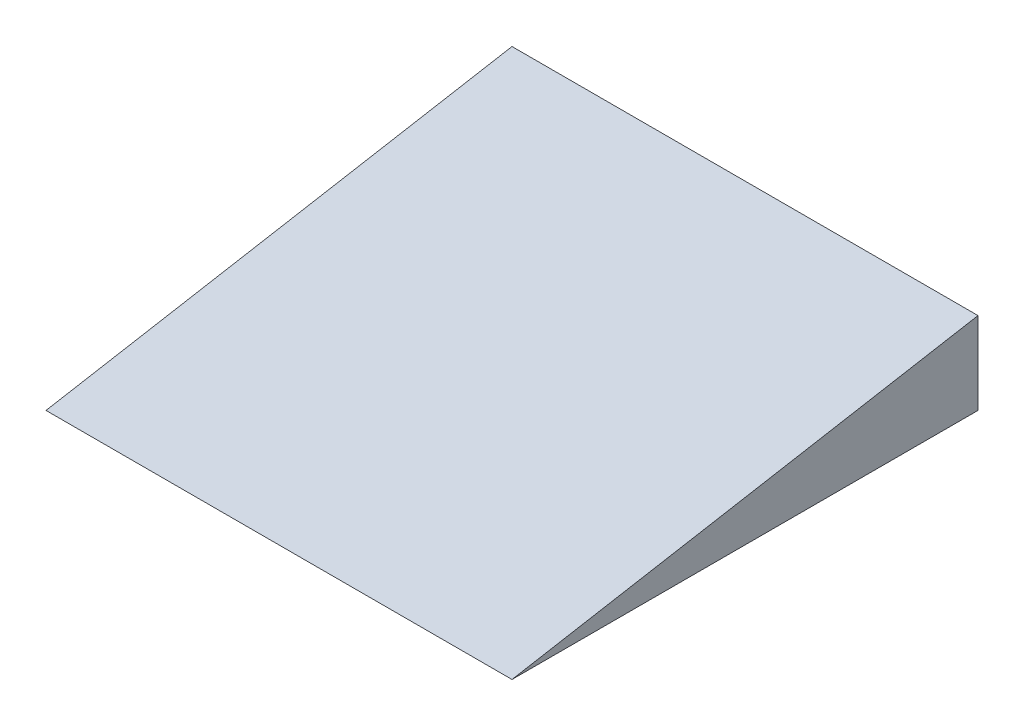
SolidWorks part; units mm, degrees
ref_plane "Front Plane" through (0, 0, 0) normal (0, 0, 1) x (1, 0, 0)
ref_plane "Top Plane" through (0, 0, 0) normal (0, 1, 0) x (1, 0, 0)
ref_plane "Right Plane" through (0, 0, 0) normal (1, 0, 0) x (0, 0, -1)
sketch "Sketch4" plane through (0, 0, 0) normal (1, 0, 0) x (0, 0, -1)
  line L0 (0, 0) -> (40, 0)
  line L1 (40, 0) -> (40, 7.0531)
  line L2 (40, 7.0531) -> (0, 0)
  dimension "D1" = 40
  dimension "D2" = 10
extrude "Boss-Extrude2" add sketch "Sketch4" along normal blind 40
